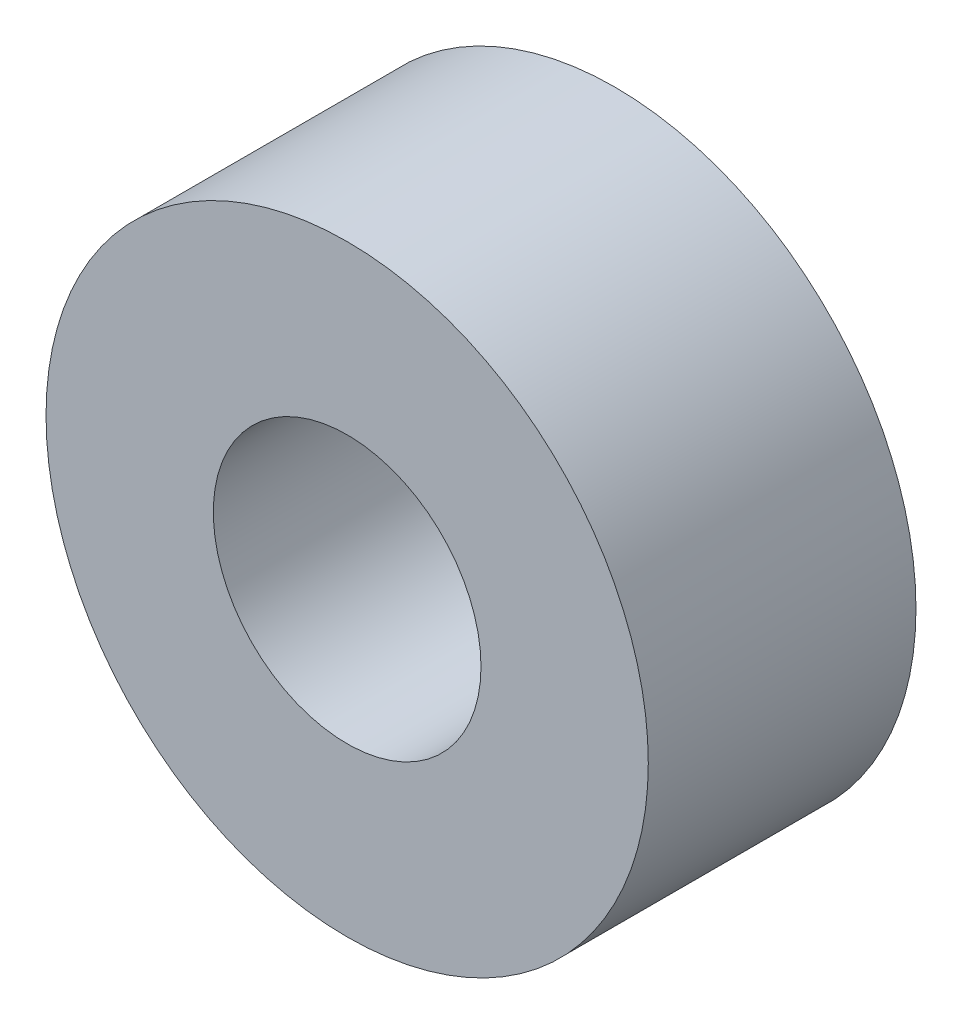
SolidWorks part; units mm, degrees
material "AISI 304"
ref_plane "Plano frontal" through (0, 0, 0) normal (0, 0, 1) x (1, 0, 0)
ref_plane "Plano superior" through (0, 0, 0) normal (0, 1, 0) x (1, 0, 0)
ref_plane "Plano direito" through (0, 0, 0) normal (1, 0, 0) x (0, 0, -1)
sketch "Esboço1" plane through (0, 0, 0) normal (0, 0, 1) x (1, 0, 0)
  circle A0 centre (0, 0) radius 4.5
  circle A1 centre (0, 0) radius 2
  dimension "D1" = 4
  dimension "D2" = 9
extrude "Ressalto-extrusão1" add sketch "Esboço1" along normal blind 4
